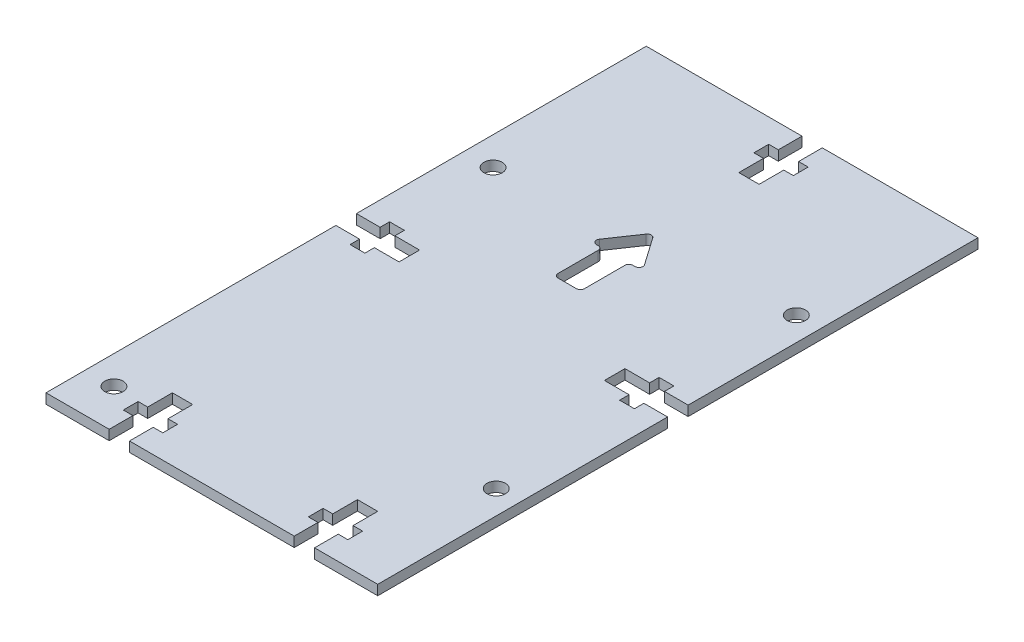
SolidWorks part; units mm, degrees
material "Acrylic (Medium-high impact)"
ref_plane "Front Plane" through (0, 0, 0) normal (0, 0, 1) x (1, 0, 0)
ref_plane "Top Plane" through (0, 0, 0) normal (0, 1, 0) x (1, 0, 0)
ref_plane "Right Plane" through (0, 0, 0) normal (1, 0, 0) x (0, 0, -1)
sketch "Sketch1" plane through (0, 0, 0) normal (0, 1, 0) x (1, 0, 0)
  line L1 (0, 0) -> (53.34, 0)
  line L2 (0, 0) -> (0, 96.52)
  line L3 (0, 96.52) -> (53.34, 96.52)
  line L4 (53.34, 0) -> (53.34, 96.52)
  dimension "D1" = 96.52
  dimension "D2" = 53.34
extrude "Boss-Extrude1" add sketch "Sketch1" along normal blind 1.6002
sketch "Sketch2" plane through (0, 1.6002, 0) normal (0, 1, 0) x (1, 0, 0)
  line L0 (10.16, 0) -> (10.16, 3.81)
  line L1 (0, 0) -> (53.34, 0) construction
  line L2 (10.16, 3.81) -> (8.6169, 3.81)
  line L3 (8.6169, 3.81) -> (8.6169, 6.1913)
  line L4 (8.6169, 6.1913) -> (10.16, 6.1913)
  line L5 (10.16, 6.1913) -> (10.16, 10.16)
  line L6 (10.16, 10.16) -> (13.4239, 10.16)
  line L7 (13.4239, 10.16) -> (13.4239, 6.1913)
  line L8 (13.4239, 6.1913) -> (14.9669, 6.1913)
  line L9 (14.9669, 6.1913) -> (14.9669, 3.81)
  line L10 (14.9669, 3.81) -> (13.4239, 3.81)
  line L11 (13.4239, 3.81) -> (13.4239, 0)
  line L12 (13.4239, 0) -> (10.16, 0)
  line L13 (0, 96.52) -> (0, 0) construction
  line L14 (26.67, 0) -> (26.67, 96.52) construction
  line L15 (53.34, 96.52) -> (0, 96.52) construction
  line L16 (0, 48.26) -> (53.34, 48.26) construction
  line L17 (53.34, 0) -> (53.34, 96.52) construction
  line L30 (28.3019, 96.52) -> (28.3019, 92.71)
  line L31 (28.3019, 92.71) -> (29.845, 92.71)
  line L32 (29.845, 92.71) -> (29.845, 90.3287)
  line L33 (29.845, 90.3287) -> (28.3019, 90.3287)
  line L34 (28.3019, 90.3287) -> (28.3019, 86.36)
  line L35 (28.3019, 86.36) -> (25.038, 86.36)
  line L36 (25.038, 86.36) -> (25.038, 90.3287)
  line L37 (25.038, 90.3287) -> (23.495, 90.3287)
  line L38 (23.495, 90.3287) -> (23.495, 92.71)
  line L39 (23.495, 92.71) -> (25.038, 92.71)
  line L40 (25.038, 92.71) -> (25.038, 96.52)
  line L41 (25.038, 96.52) -> (28.3019, 96.52)
  line L42 (39.9161, 0) -> (43.18, 0)
  line L43 (39.9161, 3.81) -> (39.9161, 0)
  line L44 (38.3731, 3.81) -> (39.9161, 3.81)
  line L45 (38.3731, 6.1913) -> (38.3731, 3.81)
  line L46 (39.9161, 6.1913) -> (38.3731, 6.1913)
  line L47 (39.9161, 10.16) -> (39.9161, 6.1913)
  line L48 (43.18, 10.16) -> (39.9161, 10.16)
  line L49 (43.18, 6.1913) -> (43.18, 10.16)
  line L50 (44.7231, 6.1913) -> (43.18, 6.1913)
  line L51 (44.7231, 3.81) -> (44.7231, 6.1913)
  line L52 (43.18, 3.81) -> (44.7231, 3.81)
  line L53 (43.18, 0) -> (43.18, 3.81)
  line L54 (0, 49.911) -> (3.81, 49.911)
  line L55 (3.81, 49.911) -> (3.81, 51.435)
  line L56 (3.81, 51.435) -> (6.1913, 51.435)
  line L57 (6.1913, 51.435) -> (6.1913, 49.911)
  line L58 (6.1913, 49.911) -> (10.16, 49.911)
  line L59 (10.16, 49.911) -> (10.16, 46.609)
  line L60 (10.16, 46.609) -> (6.1913, 46.609)
  line L61 (6.1913, 46.609) -> (6.1913, 45.085)
  line L62 (6.1913, 45.085) -> (3.81, 45.085)
  line L63 (3.81, 45.085) -> (3.81, 46.609)
  line L64 (3.81, 46.609) -> (0, 46.609)
  line L65 (0, 46.609) -> (0, 49.911)
  line L66 (53.34, 46.609) -> (53.34, 49.911)
  line L67 (49.53, 46.609) -> (53.34, 46.609)
  line L68 (49.53, 45.085) -> (49.53, 46.609)
  line L69 (47.1487, 45.085) -> (49.53, 45.085)
  line L70 (47.1487, 46.609) -> (47.1487, 45.085)
  line L71 (43.18, 46.609) -> (47.1487, 46.609)
  line L72 (43.18, 49.911) -> (43.18, 46.609)
  line L73 (47.1487, 49.911) -> (43.18, 49.911)
  line L74 (47.1487, 51.435) -> (47.1487, 49.911)
  line L75 (49.53, 51.435) -> (47.1487, 51.435)
  line L76 (49.53, 49.911) -> (49.53, 51.435)
  line L77 (53.34, 49.911) -> (49.53, 49.911)
  point P24 (26.67, 96.52)
  dimension "D1" = 10.16
  dimension "D2" = 3.2639
  dimension "D3" = 6.35
  dimension "D4" = 10.16
  dimension "D5" = 2.3813
  dimension "D6" = 3.81
  dimension "D7" = 10.16
  dimension "D8" = 6.35
  dimension "D9" = 3.81
  dimension "D10" = 3.302
  dimension "D11" = 1.651
  dimension "D12" = 1.651
  dimension "D13" = 2.3813
extrude "Cut-Extrude1" cut sketch "Sketch2" against normal blind 1.6002
hole_wizard "#32 (0.116) Diameter Hole1" positions "Sketch6" profile "Sketch5" hole size "#32" standard "ANSI Inch"
sketch "Sketch6" plane through (0, 1.6002, 0) normal (0, 1, 0) x (1, 0, 0)
  line L0 (0, 0) -> (10.16, 0) construction
  line L2 (0, 96.52) -> (0, 49.911) construction
  line L3 (43.18, 0) -> (53.34, 0) construction
  line L4 (53.34, 0) -> (53.34, 46.609) construction
  line L5 (0, 96.52) -> (0, 49.911) construction
  point P0 (4.572, 6.35)
  point P2 (49.53, 22.86)
  point P4 (49.53, 71.12)
  point P33 (4.572, 67.31)
  dimension "D1" = 6.35
  dimension "D2" = 4.572
  dimension "D3" = 22.86
  dimension "D4" = 3.81
  dimension "D5" = 3.81
  dimension "D6" = 48.26
  dimension "D7" = 60.96
  dimension "D8" = 4.572
sketch "Sketch5" plane through (4.572, 1.6002, -6.35) normal (1, 0, 0) x (0, 0, 1)
  line L0 (0, 0) -> (0, 26.2852)
  line L1 (0, 26.2852) -> (1.4732, 25.4)
  line L2 (1.4732, 25.4) -> (1.4732, 0)
  line L5 (1.4732, 0) -> (0, 0)
  line L10 (0, 26.2852) -> (-1.4732, 25.4) construction
  line L11 (0, -6.35) -> (0, 107.95) construction
  dimension "Hole Dia." = 2.9464
  dimension "Hole Depth" = 25.4
  dimension "Drill Angle" = 118
sketch "Sketch7" plane through (0, 1.6002, 0) normal (0, 1, 0) x (1, 0, 0)
  line L0 (26.67, 86.36) -> (26.67, 0) construction
  line L3 (26.67, 71.12) -> (22.4265, 64.8795)
  line L4 (22.4265, 64.8795) -> (24.5482, 64.8795)
  line L5 (24.5482, 64.8795) -> (24.5482, 57.1413)
  line L6 (24.5482, 57.1413) -> (26.67, 57.1413)
  line L7 (28.7918, 57.1413) -> (28.7918, 64.9376)
  line L8 (28.7918, 64.9376) -> (30.9977, 64.9376)
  line L9 (30.9977, 64.9376) -> (26.67, 71.12)
  line L10 (26.67, 57.1413) -> (28.7918, 57.1413)
  line L11 (25.038, 96.52) -> (0, 96.52) construction
  line L12 (25.038, 86.36) -> (28.3019, 86.36) construction
  line L13 (13.4239, 0) -> (39.9161, 0) construction
  dimension "D1" = 25.4
extrude "Cut-Extrude2" cut sketch "Sketch7" against normal blind 2.54
fillet "Fillet1" radius 0.635 7 edges at (28.7918, 0.8001, -64.9376) (24.5482, 0.8001, -64.8795) (28.7918, 0.8001, -57.1413) (24.5482, 0.8001, -57.1413) (30.9977, 0.8001, -64.9376) (22.4265, 0.8001, -64.8795) (26.67, 0.8001, -71.12)
